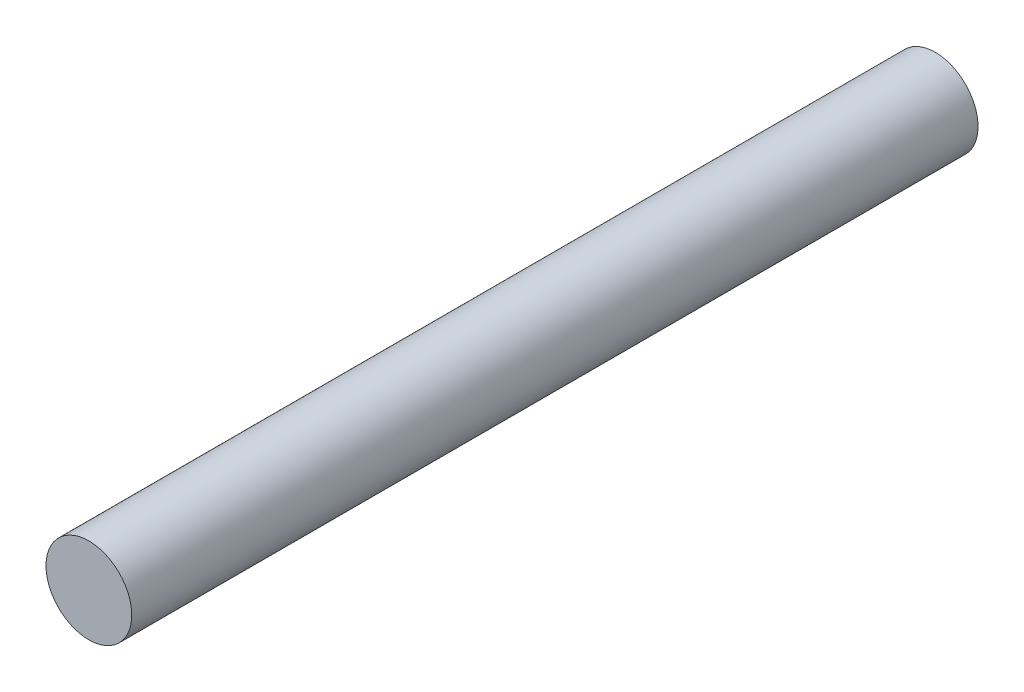
SolidWorks part; units mm, degrees
ref_plane "Front Plane" through (0, 0, 0) normal (0, 0, 1) x (1, 0, 0)
ref_plane "Top Plane" through (0, 0, 0) normal (0, 1, 0) x (1, 0, 0)
ref_plane "Right Plane" through (0, 0, 0) normal (1, 0, 0) x (0, 0, -1)
sketch "Sketch1" plane through (0, 0, 0) normal (0, 0, 1) x (1, 0, 0)
  circle A0 centre (221.8556, -9.4877) radius 6.25
  dimension "D1" = 12.5
extrude "Boss-Extrude1" add sketch "Sketch1" along normal blind 123.4
ref_plane "Plane1" through (0, 0, 61.7) normal (0, 0, 1) x (1, 0, 0)
sketch "Sketch2" plane through (0, 0, 61.7) normal (0, 0, 1) x (1, 0, 0)
  circle A0 centre (221.8556, -9.4877) radius 6.25
